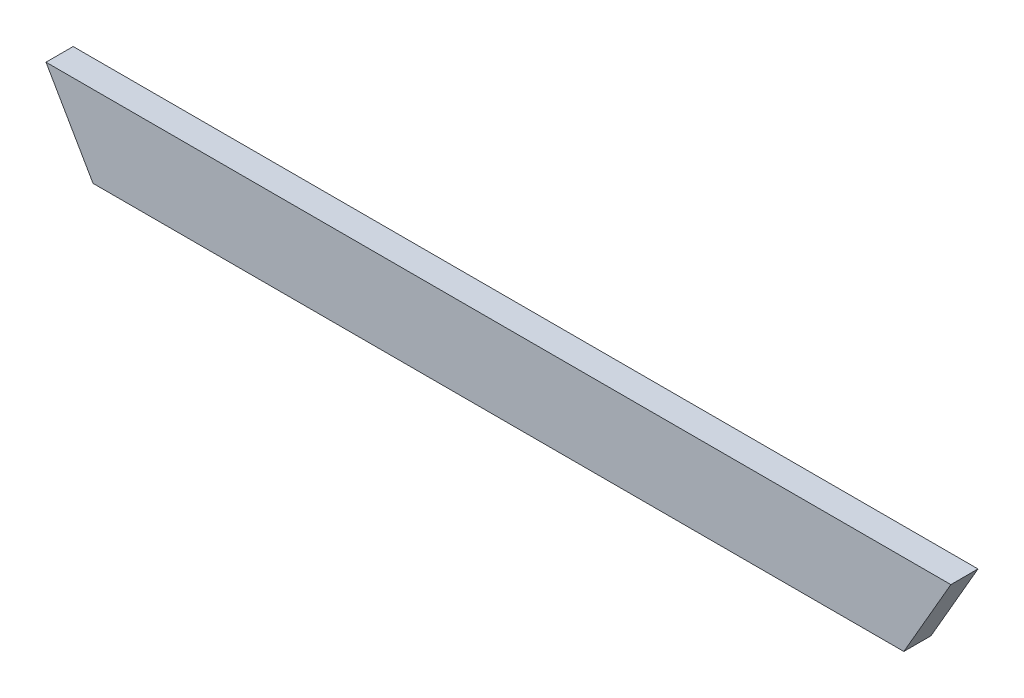
SolidWorks part; units mm, degrees
ref_plane "Plan de face" through (0, 0, 0) normal (0, 0, 1) x (1, 0, 0)
ref_plane "Plan de dessus" through (0, 0, 0) normal (0, 1, 0) x (1, 0, 0)
ref_plane "Plan de droite" through (0, 0, 0) normal (1, 0, 0) x (0, 0, -1)
sketch "Esquisse1" plane through (0, 0, 0) normal (0, 0, 1) x (1, 0, 0)
  line L0 (-225.0031, 84.1096) -> (274.9969, 84.1096)
  line L1 (274.9969, 84.1096) -> (249.0162, 39.1096)
  line L2 (249.0162, 39.1096) -> (-199.0223, 39.1096)
  line L3 (-199.0223, 39.1096) -> (-225.0031, 84.1096)
  dimension "D1" = 500
  dimension "D2" = 120
  dimension "D3" = 45
extrude "Boss.-Extru.1" add sketch "Esquisse1" along normal blind 15
